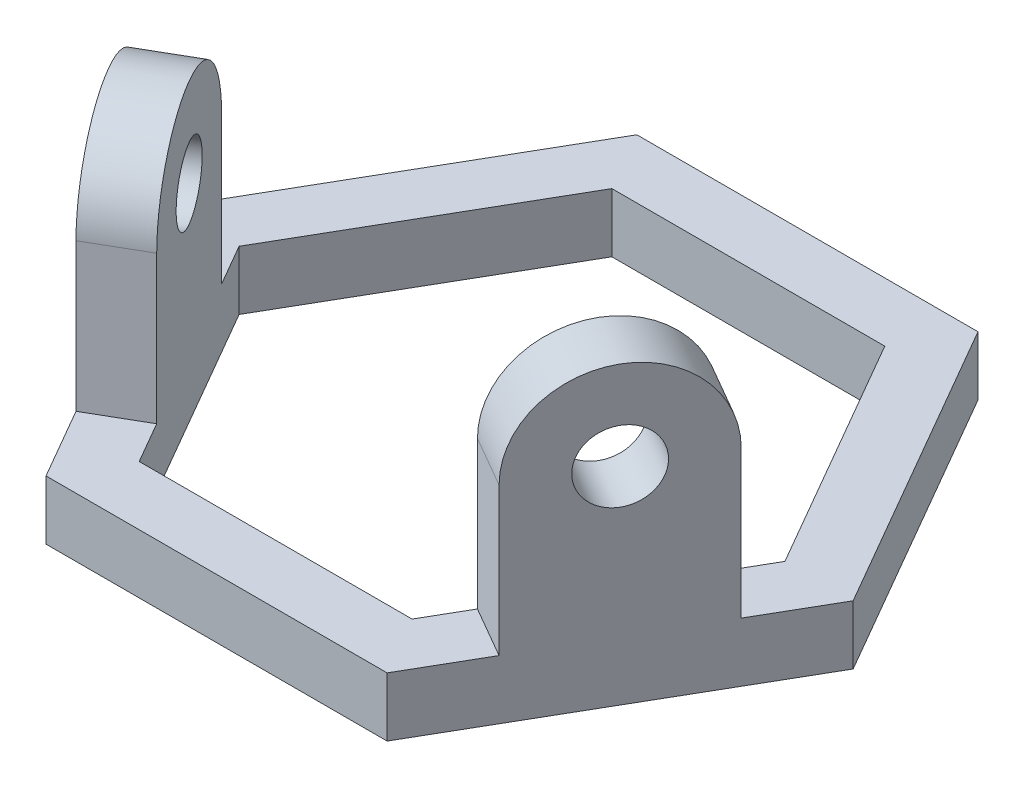
SolidWorks part; units mm, degrees
ref_plane "Płaszczyzna przednia" through (0, 0, 0) normal (0, 0, 1) x (1, 0, 0)
ref_plane "Płaszczyzna górna" through (0, 0, 0) normal (0, 1, 0) x (1, 0, 0)
ref_plane "Płaszczyzna prawa" through (0, 0, 0) normal (1, 0, 0) x (0, 0, -1)
sketch "Szkic1" plane through (0, 0, 0) normal (0, 1, 0) x (1, 0, 0)
  line L0 (23.094, 40) -> (-23.094, 40)
  line L1 (57.735, 0) -> (28.8675, 50)
  line L2 (28.8675, 50) -> (-28.8675, 50)
  line L3 (-28.8675, 50) -> (-57.735, 0)
  line L4 (-57.735, 0) -> (-28.8675, -50)
  line L5 (-28.8675, -50) -> (28.8675, -50)
  line L6 (28.8675, -50) -> (57.735, 0)
  line L7 (-23.094, 40) -> (-46.188, 0)
  line L8 (-46.188, 0) -> (-23.094, -40)
  line L9 (-23.094, -40) -> (23.094, -40)
  line L10 (23.094, -40) -> (46.188, 0)
  line L11 (46.188, 0) -> (23.094, 40)
  circle A0 centre (0, 0) radius 50 construction
  dimension "D1" = 100
  dimension "D2" = 50
  dimension "D3" = 10
extrude "Dodanie-wyciągnięcie1" add sketch "Szkic1" along normal blind 10
sketch "Szkic2" plane through (43.3013, 0, 25) normal (0.866, 0, 0.5) x (0.5, 0, -0.866)
  line L0 (-28.8675, 0) -> (28.8675, 0) construction
  line L1 (-15, 35) -> (-15, 0)
  line L2 (-15, 0) -> (15, 0)
  line L3 (15, 0) -> (15, 35)
  circle A0 centre (0, 35) radius 6
  arc A1 (-15, 35) -> (15, 35) centre (0, 35) cw
  dimension "D1" = 12
  dimension "D3" = 15
  dimension "D2" = 35
  dimension "D4" = 28.8675
extrude "Dodanie-wyciągnięcie2" add sketch "Szkic2" against normal up to surface (10 mm away) up to face at (34.641, 5, 20)
sketch "Szkic3" plane through (-43.3013, 0, 25) normal (-0.866, 0, 0.5) x (0.5, 0, 0.866)
  line L0 (0, 0) -> (0, 62.5791) construction
  line L1 (-28.8675, 0) -> (28.8675, 0) construction
  line L2 (-15, 35) -> (-15, 0)
  line L3 (-15, 0) -> (15, 0)
  line L4 (15, 0) -> (15, 35)
  circle A0 centre (0, 35) radius 6
  arc A1 (-15, 35) -> (15, 35) centre (0, 35) cw
  dimension "D1" = 12
  dimension "D3" = 15
  dimension "D2" = 35
extrude "Dodanie-wyciągnięcie3" add sketch "Szkic3" against normal up to surface (10 mm away) up to face at (-34.641, 5, 20)
